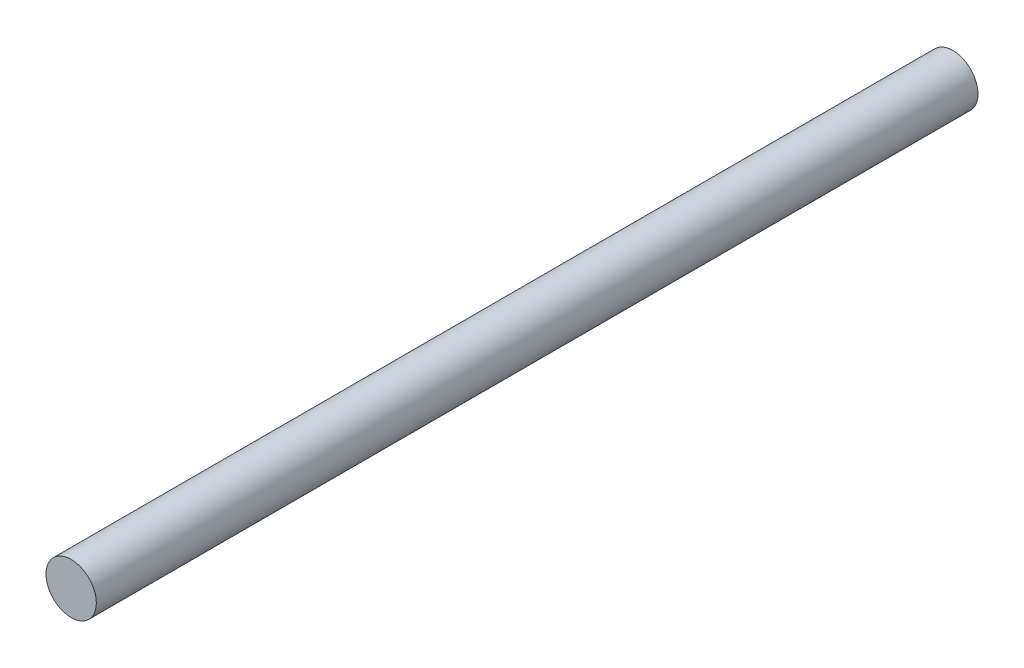
SolidWorks part; units mm, degrees
ref_plane "Front Plane" through (0, 0, 0) normal (0, 0, 1) x (1, 0, 0)
ref_plane "Top Plane" through (0, 0, 0) normal (0, 1, 0) x (1, 0, 0)
ref_plane "Right Plane" through (0, 0, 0) normal (1, 0, 0) x (0, 0, -1)
sketch "Sketch1" plane through (0, 0, 0) normal (0, 0, 1) x (1, 0, 0)
  circle A0 centre (0, 0) radius 4
  dimension "D1" = 8
extrude "Boss-Extrude1" add sketch "Sketch1" along normal blind 140
